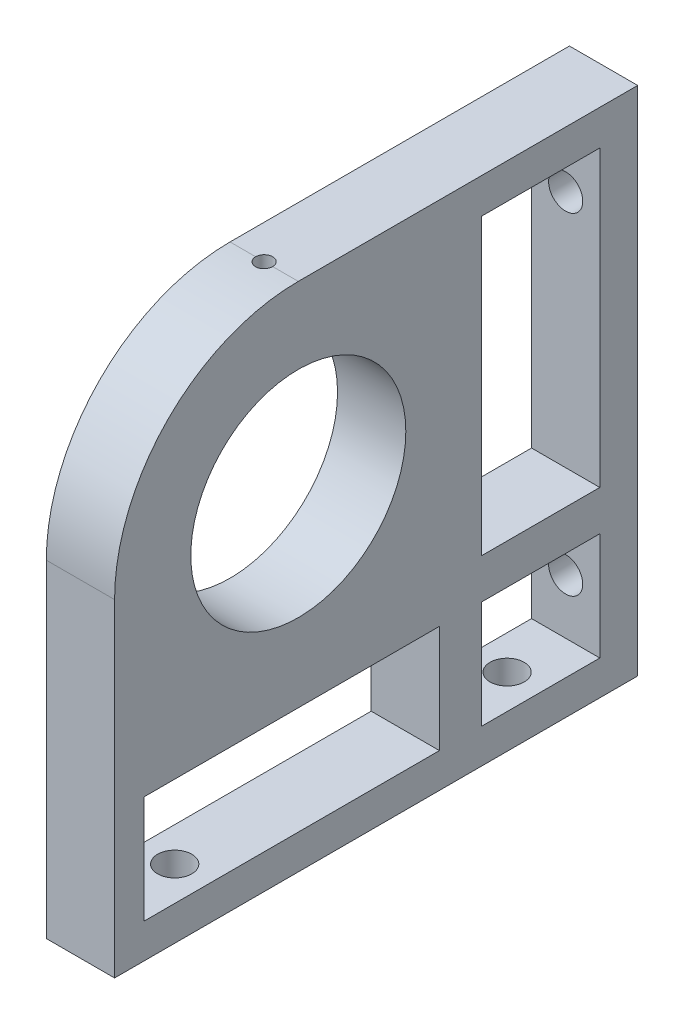
SolidWorks part; units mm, degrees
ref_plane "Front Plane" through (0, 0, 0) normal (0, 0, 1) x (1, 0, 0)
ref_plane "Top Plane" through (0, 0, 0) normal (0, 1, 0) x (1, 0, 0)
ref_plane "Right Plane" through (0, 0, 0) normal (1, 0, 0) x (0, 0, -1)
sketch "Sketch1" plane through (0, 0, 0) normal (1, 0, 0) x (0, 0, -1)
  line L13 (0, 34.1773) -> (34.1773, 34.1773)
  line L14 (34.1773, 34.1773) -> (63.1333, 34.1773)
  line L18 (63.1333, 34.1773) -> (63.1333, -60.96)
  line L19 (-34.1773, 0) -> (-34.1773, -60.96)
  line L20 (-34.1773, -60.96) -> (63.1333, -60.96)
  circle A1 centre (0, 0) radius 20
  arc A3 (0, 34.1773) -> (-34.1773, 0) centre (0, 0) ccw
extrude "Boss-Extrude1" add sketch "Sketch1" along normal blind 12.7
sketch "Sketch2" plane through (0, 0, 0) normal (0, 1, 0) x (1, 0, 0)
  circle A0 centre (6.35, 0) radius 1.5875
extrude "Cut-Extrude1" cut sketch "Sketch2" along normal through all
fillet "Fillet1" [suppressed] radius 2.54
mirror "Mirror3" [suppressed] about plane through (0, 0, 0) normal (0, 0, 1)
sketch "Sketch3" plane through (0, 0, 0) normal (-1, 0, 0) x (0, 0, 1)
  line L0 (-56.0862, 27.628) -> (-34.1045, 27.628)
  line L1 (-34.1045, 27.628) -> (-34.1045, -27.0645)
  line L2 (-26.2539, -34.5225) -> (28.7003, -34.5225)
  line L3 (28.7003, -34.5225) -> (28.7003, -54.5416)
  line L4 (28.7003, -54.5416) -> (-26.2539, -54.5416)
  line L5 (-56.0862, -54.5416) -> (-56.0862, -34.5225)
  line L6 (-34.1045, -34.5225) -> (-34.1045, -54.5416)
  line L7 (-26.2539, -54.5416) -> (-26.2539, -34.5225)
  line L8 (-34.1045, -34.5225) -> (-56.0862, -34.5225)
  line L9 (-56.0862, -27.0645) -> (-34.1045, -27.0645)
  line L10 (-56.0862, -27.0645) -> (-56.0862, 27.628)
  line L11 (-34.1045, -54.5416) -> (-56.0862, -54.5416)
extrude "Cut-Extrude2" cut sketch "Sketch3" against normal blind 70.866
sketch "Sketch4" plane through (0, -60.96, 0) normal (0, -1, 0) x (1, 0, 0)
  circle A0 centre (6.35, 16.6464) radius 3.175
  circle A1 centre (6.35, -45.1925) radius 3.175
extrude "Cut-Extrude3" cut sketch "Sketch4" against normal blind 13.462
sketch "Sketch5" plane through (0, 0, -63.1333) normal (0, 0, -1) x (-1, 0, 0)
  circle A0 centre (-6.35, 17.4451) radius 3.175
  circle A1 centre (-6.35, -44.2332) radius 3.175
extrude "Cut-Extrude4" cut sketch "Sketch5" against normal blind 13.462 contours A0 | A1
